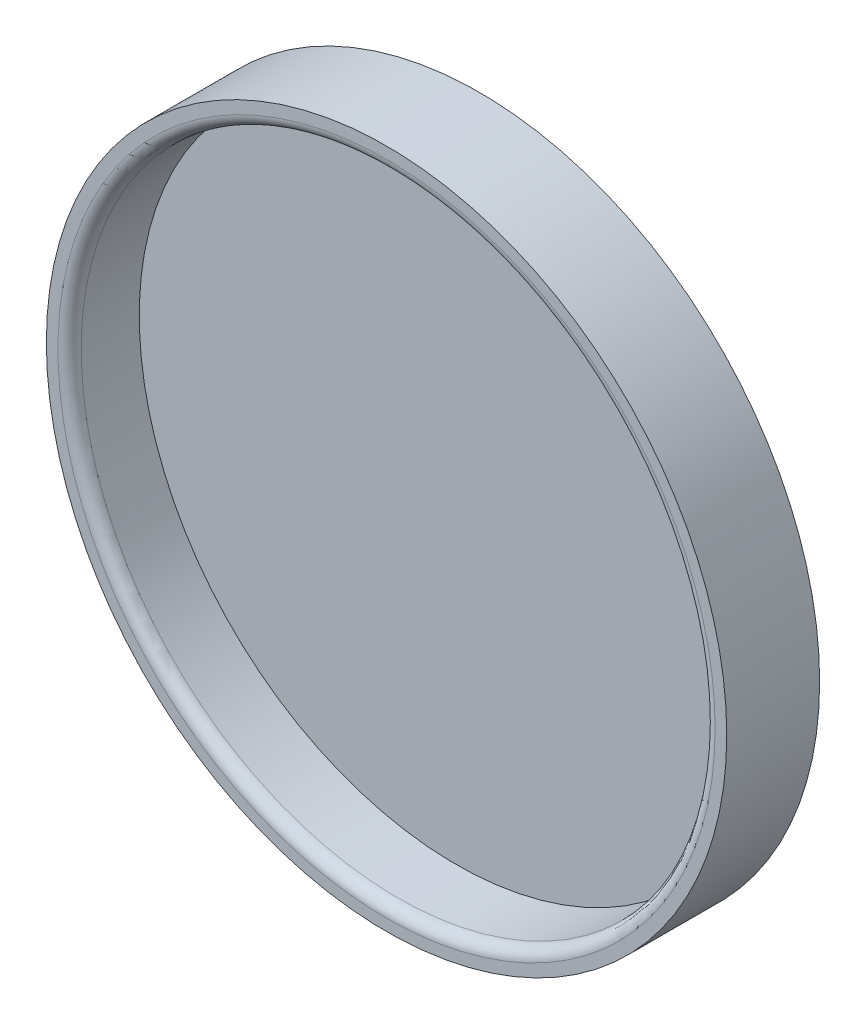
SolidWorks part; units mm, degrees
ref_plane "Front Plane" through (0, 0, 0) normal (0, 0, 1) x (1, 0, 0)
ref_plane "Top Plane" through (0, 0, 0) normal (0, 1, 0) x (1, 0, 0)
ref_plane "Right Plane" through (0, 0, 0) normal (1, 0, 0) x (0, 0, -1)
sketch "Sketch1" plane through (0, 0, 0) normal (0, 0, 1) x (1, 0, 0)
  circle A0 centre (0, 0) radius 14.65
  dimension "D1" = 29.3
extrude "Boss-Extrude1" add sketch "Sketch1" along normal blind 1
sketch "Sketch2" plane through (0, 0, 1) normal (0, 0, 1) x (1, 0, 0)
  circle A0 centre (0, 0) radius 14.65
  circle A1 centre (0, 0) radius 13.65
  circle A2 centre (0, 0) radius 14.65 construction
  dimension "D1" = 1
extrude "Boss-Extrude2" add sketch "Sketch2" along normal blind 3
fillet "Fillet1" radius 0.5 1 edges at (13.65, 0, 4)
